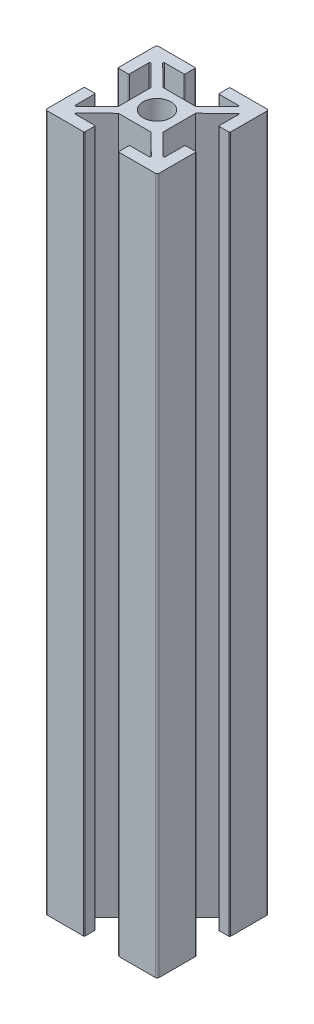
SolidWorks part; units mm, degrees
ref_plane "Front Plane" through (0, 0, 0) normal (0, 0, 1) x (1, 0, 0)
ref_plane "Top Plane" through (0, 0, 0) normal (0, 1, 0) x (1, 0, 0)
ref_plane "Right Plane" through (0, 0, 0) normal (1, 0, 0) x (0, 0, -1)
sketch "Sketch1" plane through (0, 0, 0) normal (0, 1, 0) x (1, 0, 0)
  line L0 (-9.8963, 3) -> (-8.1963, 3)
  line L3 (-3.1963, 10) -> (-9.6963, 10)
  line L4 (-10.0463, 3.15) -> (-10.0463, 9.65)
  line L7 (2.9332, 4) -> (-2.9332, 4)
  line L8 (-4, -2.9454) -> (-4, 2.9454)
  line L9 (-8.0463, 3.15) -> (-8.0463, 6.5862)
  line L10 (-6.6144, 8) -> (-3.1963, 8)
  line L11 (-3.0463, 8.15) -> (-3.0463, 9.85)
  line L12 (-8.0463, 8) -> (-4, 4) construction
  line L13 (-7.7908, 6.6929) -> (-4, 2.9454)
  line L14 (-6.7198, 7.7433) -> (-2.9332, 4)
  line L15 (8.0463, 8) -> (4, 4) construction
  line L22 (0, 0) -> (0, 11.6886) construction
  line L25 (0, 0) -> (-14.9841, 0) construction
  line L27 (6.7198, 7.7433) -> (2.9332, 4)
  line L28 (7.7908, 6.6929) -> (4, 2.9454)
  line L46 (3.0463, 8.15) -> (3.0463, 9.85)
  line L47 (6.6144, 8) -> (3.1963, 8)
  line L48 (8.0463, 3.15) -> (8.0463, 6.5862)
  line L49 (4, -2.9454) -> (4, 2.9454)
  line L50 (10.0463, 3.15) -> (10.0463, 9.65)
  line L51 (3.1963, 10) -> (9.6963, 10)
  line L52 (9.8963, 3) -> (8.1963, 3)
  line L53 (8.0463, -8) -> (4, -4) construction
  line L54 (-8.0463, -8) -> (-4, -4) construction
  line L55 (9.8963, -3) -> (8.1963, -3)
  line L56 (3.1963, -10) -> (9.6963, -10)
  line L57 (10.0463, -3.15) -> (10.0463, -9.65)
  line L58 (8.0463, -3.15) -> (8.0463, -6.5862)
  line L59 (6.6144, -8) -> (3.1963, -8)
  line L60 (3.0463, -8.15) -> (3.0463, -9.85)
  line L61 (7.7908, -6.6929) -> (4, -2.9454)
  line L62 (6.7198, -7.7433) -> (2.9332, -4)
  line L63 (-6.7198, -7.7433) -> (-2.9332, -4)
  line L64 (-7.7908, -6.6929) -> (-4, -2.9454)
  line L65 (-3.0463, -8.15) -> (-3.0463, -9.85)
  line L66 (-6.6144, -8) -> (-3.1963, -8)
  line L67 (-8.0463, -3.15) -> (-8.0463, -6.5862)
  line L68 (2.9332, -4) -> (-2.9332, -4)
  line L69 (-10.0463, -3.15) -> (-10.0463, -9.65)
  line L70 (-3.1963, -10) -> (-9.6963, -10)
  line L71 (-9.8963, -3) -> (-8.1963, -3)
  circle A0 centre (0, 0) radius 2.5
  arc A1 (-10.0463, 9.65) -> (-9.6963, 10) centre (-9.6963, 9.65) cw
  arc A2 (-9.8963, 3) -> (-10.0463, 3.15) centre (-9.8963, 3.15) cw
  arc A3 (-8.1963, 3) -> (-8.0463, 3.15) centre (-8.1963, 3.15) ccw
  arc A4 (-3.1963, 10) -> (-3.0463, 9.85) centre (-3.1963, 9.85) cw
  arc A5 (-3.1963, 8) -> (-3.0463, 8.15) centre (-3.1963, 8.15) ccw
  arc A6 (-6.7198, 7.7433) -> (-6.6144, 8) centre (-6.6144, 7.85) cw
  arc A7 (-7.7908, 6.6929) -> (-8.0463, 6.5862) centre (-7.8963, 6.5862) ccw
  arc A8 (7.7908, 6.6929) -> (8.0463, 6.5862) centre (7.8963, 6.5862) cw
  arc A9 (6.7198, 7.7433) -> (6.6144, 8) centre (6.6144, 7.85) ccw
  arc A10 (3.1963, 8) -> (3.0463, 8.15) centre (3.1963, 8.15) cw
  arc A11 (3.1963, 10) -> (3.0463, 9.85) centre (3.1963, 9.85) ccw
  arc A12 (8.1963, 3) -> (8.0463, 3.15) centre (8.1963, 3.15) cw
  arc A13 (9.8963, 3) -> (10.0463, 3.15) centre (9.8963, 3.15) ccw
  arc A14 (10.0463, 9.65) -> (9.6963, 10) centre (9.6963, 9.65) ccw
  arc A15 (10.0463, -9.65) -> (9.6963, -10) centre (9.6963, -9.65) cw
  arc A16 (9.8963, -3) -> (10.0463, -3.15) centre (9.8963, -3.15) cw
  arc A17 (8.1963, -3) -> (8.0463, -3.15) centre (8.1963, -3.15) ccw
  arc A18 (3.1963, -10) -> (3.0463, -9.85) centre (3.1963, -9.85) cw
  arc A19 (3.1963, -8) -> (3.0463, -8.15) centre (3.1963, -8.15) ccw
  arc A20 (6.7198, -7.7433) -> (6.6144, -8) centre (6.6144, -7.85) cw
  arc A21 (7.7908, -6.6929) -> (8.0463, -6.5862) centre (7.8963, -6.5862) ccw
  arc A22 (-7.7908, -6.6929) -> (-8.0463, -6.5862) centre (-7.8963, -6.5862) cw
  arc A23 (-6.7198, -7.7433) -> (-6.6144, -8) centre (-6.6144, -7.85) ccw
  arc A24 (-3.1963, -8) -> (-3.0463, -8.15) centre (-3.1963, -8.15) cw
  arc A25 (-3.1963, -10) -> (-3.0463, -9.85) centre (-3.1963, -9.85) ccw
  arc A26 (-8.1963, -3) -> (-8.0463, -3.15) centre (-8.1963, -3.15) cw
  arc A27 (-9.8963, -3) -> (-10.0463, -3.15) centre (-9.8963, -3.15) ccw
  arc A28 (-10.0463, -9.65) -> (-9.6963, -10) centre (-9.6963, -9.65) ccw
  point P8 (-10.0463, 10)
  point P27 (-10.0463, 3)
  point P30 (3.0463, 8)
  point P31 (10.0463, -10)
  point P50 (4, 0)
  point P55 (-8.0463, 3)
  point P58 (-3.0463, 10)
  point P61 (-3.0463, 8)
  point P63 (0, 4)
  point P65 (3.0463, 10)
  point P66 (8.0463, 3)
  point P67 (10.0463, 3)
  point P68 (10.0463, 10)
  point P118 (-4, 0)
  point P119 (10.0463, -3)
  point P120 (8.0463, -3)
  point P121 (3.0463, -10)
  point P122 (0, -4)
  point P123 (-3.0463, -8)
  point P124 (-3.0463, -10)
  point P125 (-8.0463, -3)
  point P126 (3.0463, -8)
  point P127 (-10.0463, -3)
  point P128 (-10.0463, -10)
  dimension "D2" = 0.35
  dimension "D3" = 0.15
  dimension "D4" = 0.15
  dimension "D5" = 0.15
  dimension "D12" = 0.15
  dimension "D13" = 0.15
  dimension "D14" = 0.15
  dimension "D6" = 2
  dimension "D7" = 7
  dimension "D8" = 7
  dimension "D9" = 2
  dimension "D10" = 0.75
  dimension "D11" = 0.75
extrude "Boss-Extrude2" add sketch "Sketch1" along normal blind 125
sketch "Sketch2" plane through (0, 0, 4) normal (0, 0, 1) x (1, 0, 0)
  line L0 (0, 0) -> (0, 125) construction
  line L1 (-2.9332, 125) -> (2.9332, 125) construction
  circle A0 centre (0, 115.3629) radius 2
  circle A2 centre (0, 75.3629) radius 2
  dimension "D1" = 40
  dimension "D2" = 4
  dimension "D3" = 4
extrude "Cut-Extrude1" cut sketch "Sketch2" against normal blind 5
